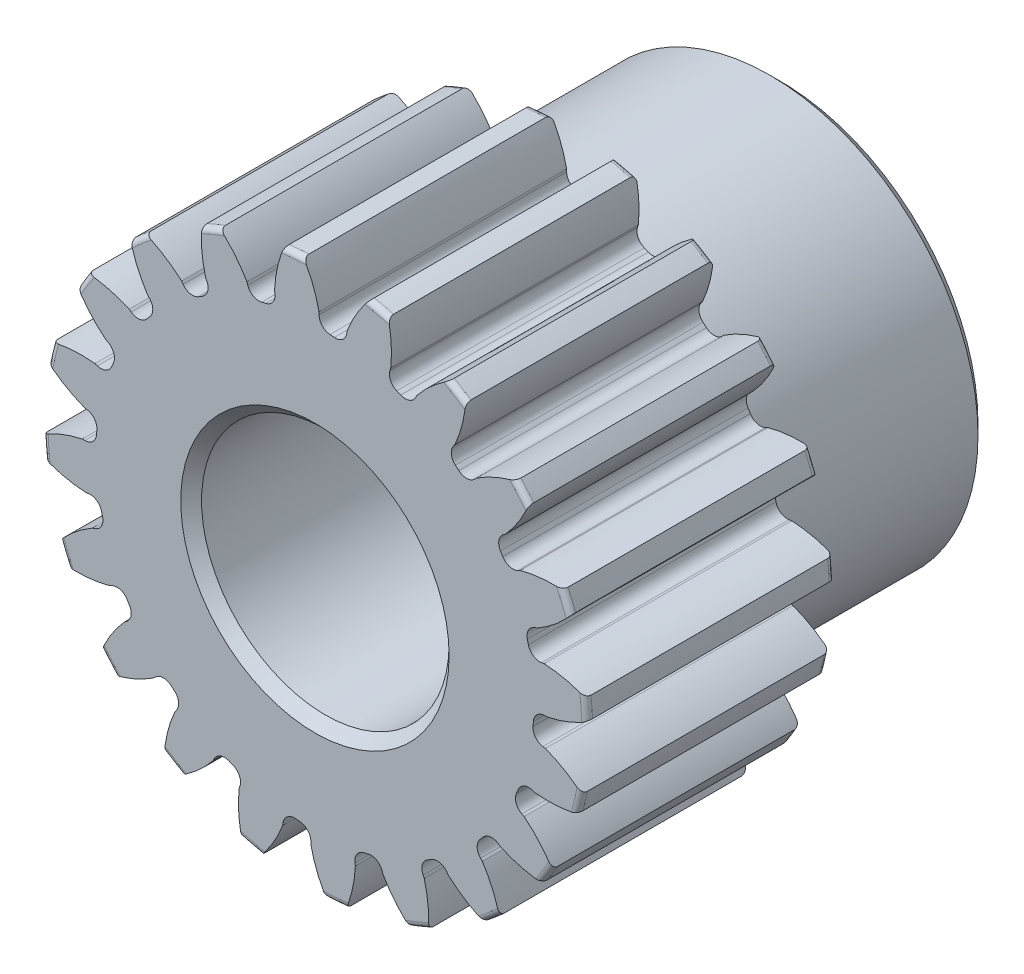
SolidWorks part; units mm, degrees
ref_plane "Front" through (0, 0, 0) normal (0, 0, 1) x (1, 0, 0)
ref_plane "Top" through (0, 0, 0) normal (0, 1, 0) x (1, 0, 0)
ref_plane "Right" through (0, 0, 0) normal (1, 0, 0) x (0, 0, -1)
sketch "Sketch1" plane through (0, 0, 0) normal (0, 0, 1) x (1, 0, 0)
  line L0 (-254, 0) -> (254, 0) construction
  circle A0 centre (0, 0) radius 13.97
  circle A1 centre (0, 0) radius 12.7 construction
  circle A3 centre (0, 0) radius 11.2306 construction
  dimension "D1" = 1.4694
  dimension "OD" = 27.94
  dimension "Ptich Dia" = 25.4
  dimension "D2" = 2.7394
  dimension "Root Dia" = 22.4612
  dimension "D3" = 1.27
  dimension "Number of Teeth" = 508
extrude "Boss-Extrude1" add sketch "Sketch1" against normal blind 12.7
sketch "Sketch2" plane through (0, 0, 0) normal (1, 0, 0) x (0, 0, -1)
  line L0 (12.7, 0) -> (23.876, 0)
  line L1 (12.7, 0) -> (12.7, 10.668)
  line L2 (12.7, 10.668) -> (23.876, 10.668)
  line L3 (23.876, 10.668) -> (23.876, 0)
  point P5 (23.876, -10.668)
  point P6 (0, -13.97)
  point P7 (12.7, -13.97)
  point P9 (0, 13.97)
  dimension "Face Wd" = 12.7
  dimension "B Hub Dia" = 21.336
  dimension "D O'all Lg." = 23.876
revolve "Revolve1" add sketch "Sketch2" angle 360 mid plane about L0
fillet "Fillet2" radius 0.2794 3 edges at (13.97, 0, -12.7) (13.97, 0, 0) (10.668, 0, -12.7)
sketch "Sketch3" plane through (0, 0, 0) normal (0, 0, 1) x (1, 0, 0)
  line L0 (0, 0) -> (0, 13.97) construction
  line L1 (-4.0817, 11.2144) -> (0, 12.7)
  line L2 (-9.5921, 12.7) -> (9.5921, 12.7) construction
  line L3 (-9.0136, 9.4193) -> (9.0136, 15.9807) construction
  line L4 (-4.0817, 11.2144) -> (0, 0) construction
  line L5 (-9.951, 6.5878) -> (0, 0) construction
  line L6 (-9.951, 6.5878) -> (-3.3571, 16.548) construction
  line L7 (-2.8353, 11.5924) -> (0, 0) construction
  line L8 (-2.8353, 11.5924) -> (0.1182, 12.3148) construction
  arc A0 (-4.0817, 11.2144) -> (-9.951, 6.5878) centre (0, 0) ccw
  circle A1 centre (0, 0) radius 12.7 construction
  circle A2 centre (0, 0) radius 11.9341 construction
  arc A3 (-4.0817, 11.2144) -> (-2.8353, 11.5924) centre (0, 0) cw
  circle A4 centre (0, 0) radius 13.97 construction
  point P6 (0, 12.7)
  dimension "D1" = 4.3437
  dimension "Pressure Angle" = 20
  dimension "D2" = 7.6014
  dimension "D3" = 11.9451
  dimension "D4" = 1.3031
  dimension "D5" = 3.0406
sketch "Sketch4" plane through (0, 0, 0) normal (0, 0, 1) x (1, 0, 0)
  line L0 (0, 0) -> (0.9934, 12.6218) construction
  line L1 (0.2108, 11.9322) -> (0.2108, 11.2286)
  line L2 (0, 12.7) -> (1.9867, 12.5436) construction
  line L3 (1.6584, 11.8183) -> (1.5483, 11.1234)
  line L4 (0.2108, 11.2286) -> (0, 0) construction
  line L5 (0, 0) -> (0, 13.97) construction
  line L6 (-9.951, 6.5878) -> (-3.3571, 16.548) construction
  line L7 (-9.951, 6.5878) -> (-3.3571, 16.548) construction
  arc A0 (1.5483, 11.1234) -> (0.2108, 11.2286) centre (0, 0) ccw
  arc A1 (0, 12.7) -> (1.9867, 12.5436) centre (0, 0) cw construction
  circle A2 centre (0, 0) radius 12.7 construction
  circle A3 centre (0, 0) radius 11.9341 construction
  circle A4 centre (0, 0) radius 11.2306 construction
  arc A5 (5.9045, 15.8191) -> (-3.3571, 16.548) centre (0, 0) ccw
  spline S0 degree 2 poles (-3.3571, 16.548) (-0.4015, 14.8243) (0.2108, 11.9322) knots 0 0 0 1 1 1
  spline S1 degree 2 poles (5.9045, 15.8191) (2.7156, 14.579) (1.6584, 11.8183) knots 0 0 0 1 1 1
  dimension "D1" = 1.9949
extrude "Cut-Extrude1" cut sketch "Sketch4" against normal through all
fillet "Fillet1" radius 0.5985 2 edges at (1.5483, 11.1234, -6.35) (0.2108, 11.2286, -6.35)
pattern_circular "CirPattern1" count 20 over 360 about axis through (0, 0, -12.7) along (0, 0, 1) of "Cut-Extrude1", "Fillet1"
sketch "Sketch5" plane through (0, 0, 0) normal (0, 0, 1) x (1, 0, 0)
  circle A0 centre (0, 0) radius 6.35
  circle A1 centre (0, 0) radius 6.35 construction
  dimension "Bore Min" = 12.7
  dimension "Bore Max" = 12.7
extrude "Cut-Extrude2" cut sketch "Sketch5" against normal through all
chamfer "Chamfer1" distance 0.5334 angle 45 3 edges at (10.668, 0, -23.876) (6.35, 0, 0) (6.35, 0, -23.876)
sketch "Pitch Dia" plane through (0, 0, 0) normal (0, 0, 1) x (1, 0, 0)
  circle A0 centre (0, 0) radius 12.7 construction
  circle A1 centre (0, 0) radius 12.7 construction
equation "\"D1@Boss-Extrude1\" = \"Face Wd@Sketch2\""
equation "\"D2@Sketch3\" = \"D1@Sketch3\"*1.75"
equation "\"D3@Sketch3\" = \"D1@Sketch3\"+\"D2@Sketch3\""
equation "\"D4@Sketch3\" = \"D1@Sketch3\"*.3"
equation "\"D5@Sketch3\" = \"D1@Sketch3\"-\"D4@Sketch3\""
equation "\"D1@Sketch4\" = 1.5708/(\"Number of Teeth@Sketch1\"/\"Ptich Dia@Sketch1\")"
equation "\"D1@Chamfer1\" = \"B Hub Dia@Sketch2\"*.025"
equation "\"D1@CirPattern1\" = \"Number of Teeth@Sketch1\""
equation "\"D1@Fillet1\" = \"D1@Sketch4\"*.3"
equation "\"D1@Fillet2\" = \"OD@Sketch1\"*.01"
equation "\"D1@Sketch1\" = 1.157/(\"Number of Teeth@Sketch1\"/\"Ptich Dia@Sketch1\")"
